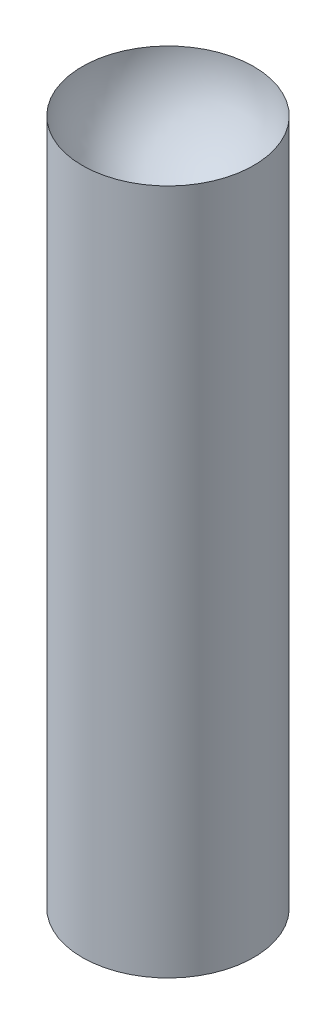
SolidWorks part; units mm, degrees
ref_plane "Front Plane" through (0, 0, 0) normal (0, 0, 1) x (1, 0, 0)
ref_plane "Top Plane" through (0, 0, 0) normal (0, 1, 0) x (1, 0, 0)
ref_plane "Right Plane" through (0, 0, 0) normal (1, 0, 0) x (0, 0, -1)
sketch "Sketch1" plane through (0, 0, 0) normal (0, 1, 0) x (1, 0, 0)
  circle A0 centre (0, 0) radius 12.7
extrude "Boss-Extrude1" add sketch "Sketch1" along normal blind 101.6
sketch "Sketch2" plane through (0, 101.6, 0) normal (0, 1, 0) x (1, 0, 0)
  line L0 (0, 12.7) -> (0, -12.7) construction
  line L1 (0, 12.7) -> (0, -12.7)
  arc A0 (0, -12.7) -> (0, 12.7) centre (0, 0) ccw
revolve "Cut-Revolve1" cut sketch "Sketch2" angle 360 about L0
sketch "Sketch3" plane through (0, 0, 0) normal (0, -1, 0) x (-1, 0, 0)
  line L0 (0, -10.16) -> (0, 10.16) construction
  line L1 (0, -10.16) -> (0, 10.16)
  arc A0 (0, 10.16) -> (0, -10.16) centre (0, 0) ccw
revolve "Cut-Revolve2" cut sketch "Sketch3" angle 360 about L0
